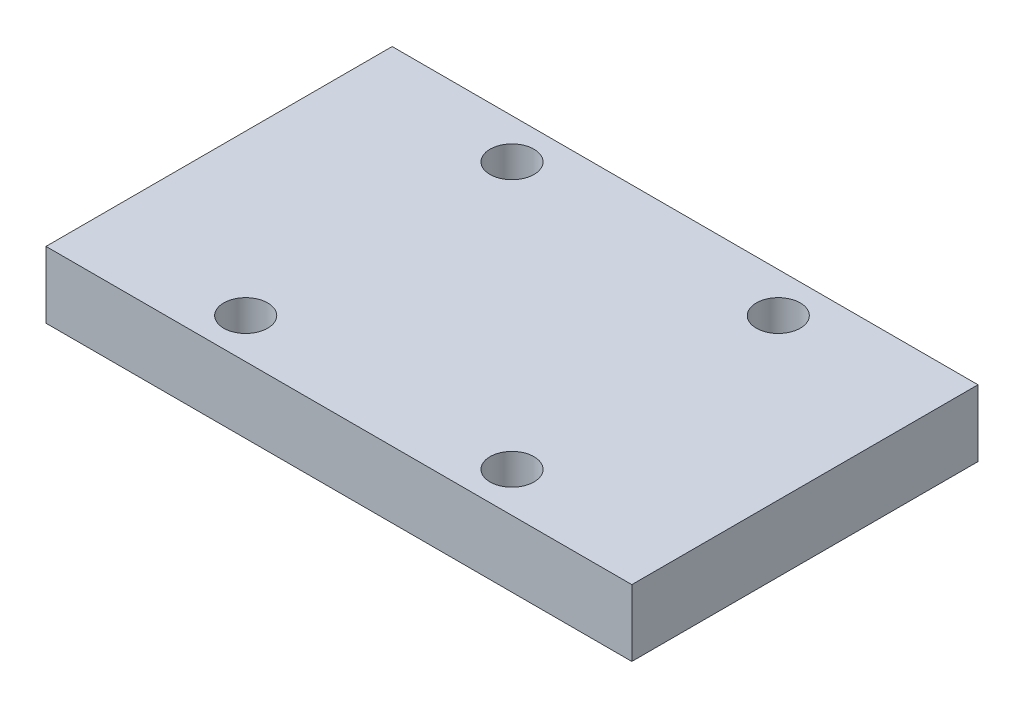
SolidWorks part; units mm, degrees
ref_plane "Plan de face" through (0, 0, 0) normal (0, 0, 1) x (1, 0, 0)
ref_plane "Plan de dessus" through (0, 0, 0) normal (0, 1, 0) x (1, 0, 0)
ref_plane "Plan de droite" through (0, 0, 0) normal (1, 0, 0) x (0, 0, -1)
sketch "Sketch2" plane through (0, 0, 0) normal (0, 1, 0) x (1, 0, 0)
  line L0 (10, 0) -> (10, -10) construction
  line L1 (0, 0) -> (22, 0) construction
  line L2 (0, 0) -> (0, -13) construction
  line L3 (-22, -13) -> (22, -13)
  line L4 (22, 13) -> (22, -13)
  line L5 (10, -10) -> (0, -10) construction
  line L6 (5.875, -4.75) -> (14.125, -4.75)
  line L7 (14.125, -4.75) -> (14.125, -13)
  line L8 (5.875, -4.75) -> (5.875, -13)
  line L9 (5.875, 4.75) -> (5.875, 13)
  line L10 (14.125, 4.75) -> (14.125, 13)
  line L11 (5.875, 4.75) -> (14.125, 4.75)
  line L12 (-22, 13) -> (22, 13)
  line L13 (-5.875, 4.75) -> (-14.125, 4.75)
  line L14 (-14.125, 4.75) -> (-14.125, 13)
  line L15 (-5.875, 4.75) -> (-5.875, 13)
  line L16 (-5.875, -4.75) -> (-5.875, -13)
  line L17 (-14.125, -4.75) -> (-14.125, -13)
  line L18 (-5.875, -4.75) -> (-14.125, -4.75)
  line L19 (-22, 13) -> (-22, -13)
  circle A0 centre (10, -10) radius 1.65
  circle A1 centre (10, 10) radius 1.65
  circle A2 centre (-10, 10) radius 1.65
  circle A3 centre (-10, -10) radius 1.65
  point P13 (10, -4.75)
  point P22 (10, 4.75)
  point P28 (0, 13)
  point P37 (-10, 4.75)
  point P38 (-10, -4.75)
  dimension "D4" = 3.3
  dimension "D1" = 22
  dimension "D2" = 13
  dimension "D3" = 10
  dimension "D5" = 8.25
extrude "Boss-Extrude1" add sketch "Sketch2" against normal blind 5 contours L13 L15 L12 L14 A2 | L12 L19 L3 L17 L18 L16 L8 L6 L7 L4 L10 L11 L9 L15 L13 L14 | L12 L9 L11 L10 A1 | L6 L8 L3 L7 A0 | L16 L18 L17 L3 A3
